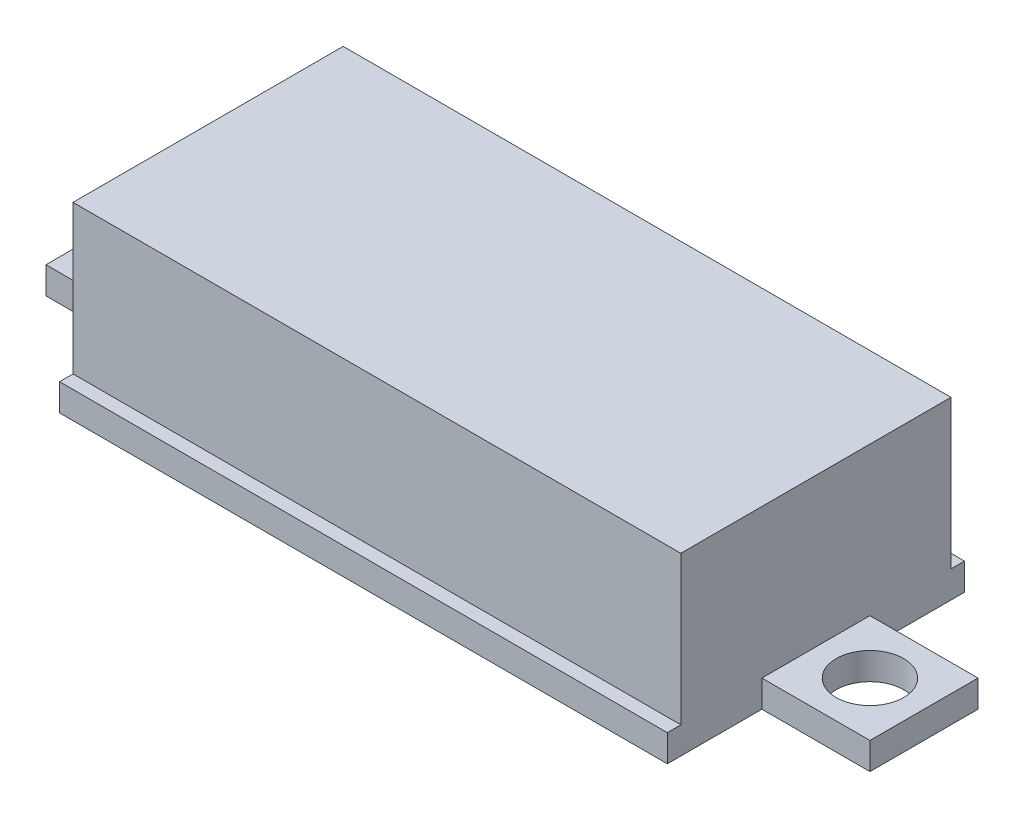
SolidWorks part; units mm, degrees
ref_plane "Front" through (0, 0, 0) normal (0, 0, 1) x (1, 0, 0)
ref_plane "Top" through (0, 0, 0) normal (0, 1, 0) x (1, 0, 0)
ref_plane "Right" through (0, 0, 0) normal (1, 0, 0) x (0, 0, -1)
sketch "Эскиз1" plane through (0, 0, 0) normal (0, 1, 0) x (1, 0, 0)
  line L0 (-15.25, 0) -> (15.25, 0) construction
  line L1 (-11.25, 5.5) -> (11.25, 5.5)
  line L2 (-11.25, 5.5) -> (-11.25, -5.5)
  line L3 (-11.25, -5.5) -> (11.25, -5.5)
  line L4 (11.25, 5.5) -> (11.25, -5.5)
  line L5 (-11.25, 5.5) -> (11.25, -5.5) construction
  line L6 (-11.25, -5.5) -> (11.25, 5.5) construction
  line L7 (-11.25, 2) -> (-15.25, 2)
  line L8 (-11.25, 2) -> (-11.25, -2)
  line L9 (-11.25, -2) -> (-15.25, -2)
  line L10 (-15.25, 2) -> (-15.25, -2)
  line L11 (11.25, 2) -> (15.25, 2)
  line L12 (11.25, 2) -> (11.25, -2)
  line L13 (11.25, -2) -> (15.25, -2)
  line L14 (15.25, 2) -> (15.25, -2)
  line L15 (0, 5.5) -> (0, -5.5) construction
  circle A0 centre (-13.25, 0) radius 1.25
  circle A1 centre (13.25, 0) radius 1.25
  point P0 (0, 0)
  dimension "D5" = 2.5
  dimension "D1" = 22.5
  dimension "D2" = 11
  dimension "D3" = 30.5
  dimension "D4" = 4
  dimension "D6" = 26.5
extrude "Бобышка-Вытянуть1" add sketch "Эскиз1" along normal blind 1 contours L4 L1 L2 L3 | A1 | A0 | L10 L9 L8 L7 | L13 L14 L11 L12
sketch "Эскиз2" plane through (0, 1, 0) normal (0, 1, 0) x (1, 0, 0)
  line L1 (-11.25, 5) -> (11.25, 5)
  line L2 (-11.25, 5) -> (-11.25, -5)
  line L3 (-11.25, -5) -> (11.25, -5)
  line L4 (11.25, 5) -> (11.25, -5)
  line L5 (-11.25, 5) -> (11.25, -5) construction
  line L6 (-11.25, -5) -> (11.25, 5) construction
  point P0 (0, 0)
  dimension "D1" = 10
  dimension "D2" = 22.5
extrude "Бобышка-Вытянуть2" add sketch "Эскиз2" along normal blind 5.5
